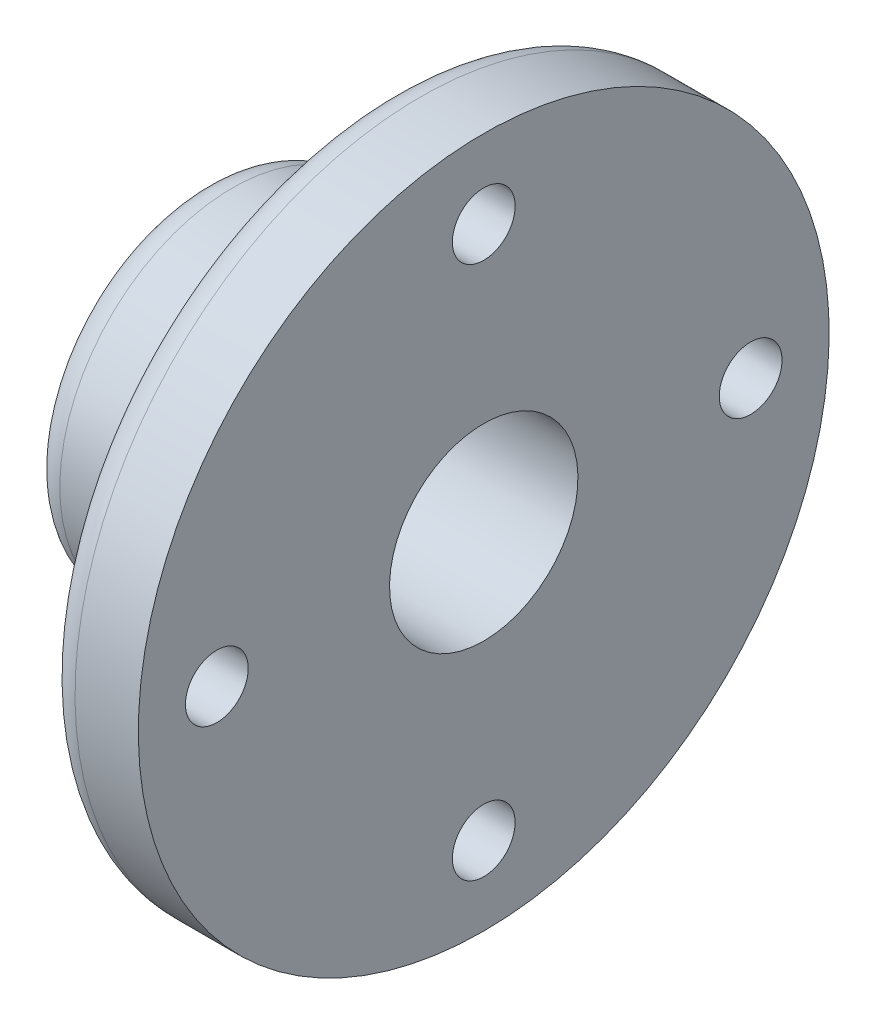
SolidWorks part; units mm, degrees
ref_plane "Front Plane" through (0, 0, 0) normal (0, 0, 1) x (1, 0, 0)
ref_plane "Top Plane" through (0, 0, 0) normal (0, 1, 0) x (1, 0, 0)
ref_plane "Right Plane" through (0, 0, 0) normal (1, 0, 0) x (0, 0, -1)
sketch "Sketch1" plane through (0, 0, 0) normal (0, 0, 1) x (1, 0, 0)
  line L0 (0, 76.5697) -> (0, -73.7404) construction
  line L1 (-117.2741, 0) -> (111.1973, 0) construction
  line L2 (-55.118, 19.05) -> (0, 19.05)
  line L3 (0, 19.05) -> (0, 69.85)
  line L4 (0, 69.85) -> (-12.8016, 69.85)
  line L5 (-19.1516, 63.5) -> (-19.1516, 41.275)
  line L6 (-25.5016, 34.925) -> (-50.8, 34.925)
  line L7 (-57.15, 28.575) -> (-57.15, 21.082)
  line L8 (-57.15, 21.082) -> (-55.118, 19.05)
  arc A0 (-25.5016, 34.925) -> (-19.1516, 41.275) centre (-25.5016, 41.275) ccw
  arc A1 (-19.1516, 63.5) -> (-12.8016, 69.85) centre (-12.8016, 63.5) cw
  arc A2 (-57.15, 28.575) -> (-50.8, 34.925) centre (-50.8, 28.575) cw
  point P5 (-57.15, 19.05)
  dimension "D6" = 6.35
  dimension "D7" = 6.35
  dimension "D8" = 6.35
  dimension "D1" = 139.7
  dimension "D2" = 69.85
  dimension "D3" = 19.1516
  dimension "D4" = 38.1
  dimension "D5" = 57.15
  dimension "D9" = 2.032
  dimension "D10" = 45
revolve "Revolve1" add sketch "Sketch1" angle 360 about L1
sketch "Sketch2" plane through (-19.1516, 0, 0) normal (-1, 0, 0) x (0, 0, 1)
  circle A0 centre (0, 0) radius 53.975 construction
  circle A1 centre (0, 53.975) radius 6.35
  dimension "D1" = 107.95
  dimension "D2" = 12.7
extrude "Cut-Extrude1" cut sketch "Sketch2" against normal through all
pattern_circular "CirPattern1" count 4 over 360 about axis through (0, 0, 0) along (1, 0, 0) of "Cut-Extrude1"
